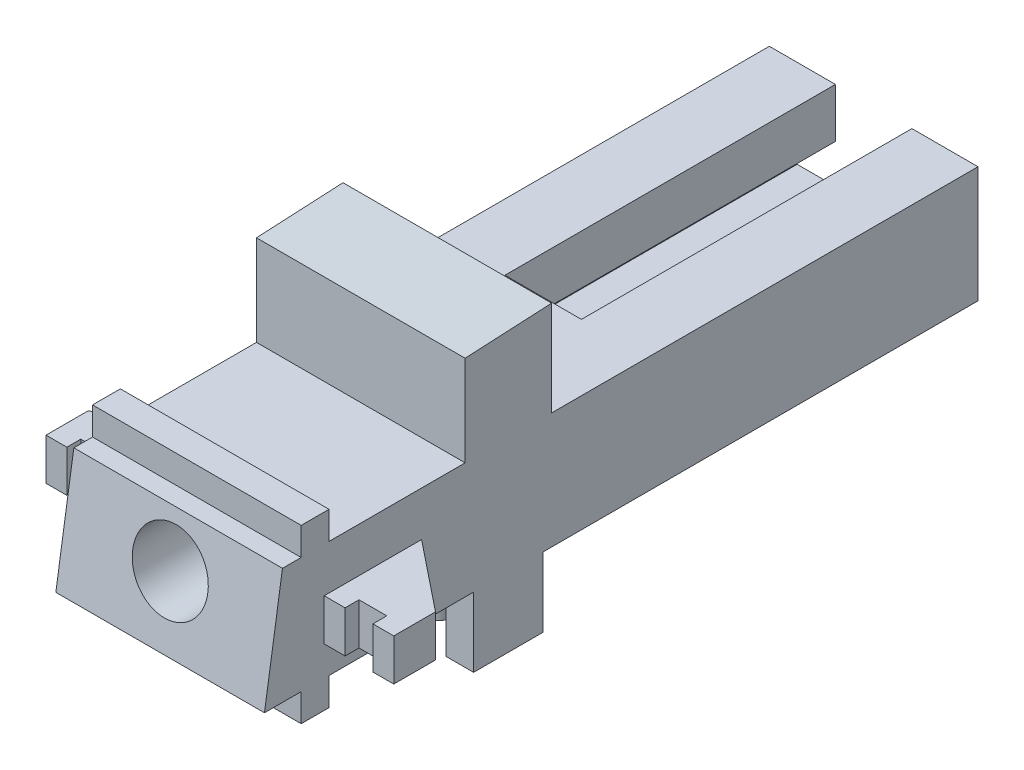
SolidWorks part; units mm, degrees
ref_plane "Front Plane" through (0, 0, 0) normal (0, 0, 1) x (1, 0, 0)
ref_plane "Top Plane" through (0, 0, 0) normal (0, 1, 0) x (1, 0, 0)
ref_plane "Right Plane" through (0, 0, 0) normal (1, 0, 0) x (0, 0, -1)
sketch "Sketch9" plane through (0, 0, 0) normal (0, 0, 1) x (1, 0, 0)
  line L1 (-7.5, 8.35) -> (7.5, 8.35)
  line L2 (-7.5, 8.35) -> (-7.5, 0)
  line L3 (-7.5, 0) -> (7.5, 0)
  line L4 (7.5, 8.35) -> (7.5, 0)
  line L5 (-7.5, 8.35) -> (7.5, 0) construction
  line L6 (-7.5, 0) -> (7.5, 8.35) construction
  point P0 (0, 4.175)
  point P19 (0, 0)
  dimension "D1" = 8.35
  dimension "D2" = 15
extrude "Boss-Extrude4" add sketch "Sketch9" along normal blind 50
sketch "Sketch7" plane through (0, 0, 0) normal (0, 0, 1) x (1, 0, 0)
  line L0 (-5.5, 2) -> (-5.5, 4.8)
  line L1 (-5.5, 4.8) -> (-2.75, 4.8)
  line L2 (-2.75, 4.8) -> (-2.75, 8.35)
  line L3 (-2.75, 8.35) -> (2.75, 8.35) construction
  line L4 (2.75, 8.35) -> (2.75, 4.8)
  line L5 (2.75, 4.8) -> (5.5, 4.8)
  line L6 (5.5, 4.8) -> (5.5, 2)
  line L7 (5.5, 2) -> (-5.5, 2)
  line L9 (7.5, 8.35) -> (-7.5, 8.35) construction
  line L11 (7.5, 0) -> (7.5, 8.35) construction
  line L13 (-2.75, 8.35) -> (2.75, 8.35)
  dimension "D1" = 2.8
  dimension "D2" = 2
  dimension "D3" = 11
  dimension "D4" = 5.5
  dimension "D5" = 2
extrude "Cut-Extrude4" cut sketch "Sketch7" along normal blind 23.76
sketch "Sketch21" plane through (-7.5, 0, 0) normal (-1, 0, 0) x (0, 0, 1)
  line L7 (50, 0) -> (51.2947, 0)
  line L8 (51.2947, 0) -> (50, 8.35)
  line L9 (50, 8.35) -> (50, 0)
extrude "Boss-Extrude9" add sketch "Sketch21" against normal up to surface (15 mm away) up to face at (7.5, 4.175, 25)
sketch "Sketch10" plane through (0, 0, 23.76) normal (0, 0, 1) x (1, 0, 0)
  line L0 (5.5, 2) -> (-5.5, 2) construction
  circle A0 centre (0, 4.7) radius 2.7
  dimension "D1" = 5.4
extrude "Cut-Extrude5" cut sketch "Sketch10" along normal up to surface (26.806 mm away)
sketch "Sketch12" plane through (7.5, 0, 0) normal (1, 0, 0) x (0, 0, -1)
  line L0 (-51.2947, 0) -> (0, 0) construction
  line L1 (-47, 5.14) -> (-44, 5.14)
  line L2 (-47, 5.14) -> (-47, 2.14)
  line L3 (-47, 2.14) -> (-44, 2.14)
  line L4 (-44, 5.14) -> (-44, 2.14)
  line L5 (-47, 5.14) -> (-44, 2.14) construction
  line L6 (-47, 2.14) -> (-44, 5.14) construction
  point P0 (-45.5, 3.64)
  dimension "D1" = 3
  dimension "D2" = 3
  dimension "D3" = 2.14
  dimension "D4" = 3
extrude "Boss-Extrude5" add sketch "Sketch12" along normal blind 5
ref_plane "Plane1" through (0, 0, 0) normal (1, 0, 0) x (0, 0, -1)
sketch "Sketch13" plane through (0, 0, 47) normal (0, 0, 1) x (1, 0, 0)
  line L1 (9, 5.14) -> (11, 5.14)
  line L2 (9, 5.14) -> (9, 2.14)
  line L3 (9, 2.14) -> (11, 2.14)
  line L4 (11, 5.14) -> (11, 2.14)
  line L6 (12.5, 5.14) -> (7.5, 5.14) construction
  line L7 (12.5, 2.14) -> (7.5, 2.14) construction
  point P8 (10, 5.14)
  point P9 (10, 5.14)
  dimension "D2" = 2
extrude "Cut-Extrude6" cut sketch "Sketch13" against normal blind 1
mirror "Mirror2" about plane through (0, 0, 0) normal (1, 0, 0) of "Boss-Extrude5"
mirror "Mirror4" about plane through (0, 0, 0) normal (1, 0, 0) of "Cut-Extrude6"
sketch "Sketch14" plane through (0, 5.14, 0) normal (0, 1, 0) x (1, 0, 0)
  line L0 (12.5, -44) -> (7.5, -40)
  line L1 (7.5, -50) -> (7.5, 0) construction
  line L2 (7.5, -40) -> (7.5, -44)
  line L3 (7.5, -44) -> (12.5, -44)
  dimension "D1" = 4
extrude "Boss-Extrude6" add sketch "Sketch14" against normal up to surface (3 mm away) up to face at (10, 2.14, 46)
mirror "Mirror5" about plane through (0, 0, 0) normal (1, 0, 0) of "Boss-Extrude6"
sketch "Sketch22" plane through (-7.5, 0, 0) normal (-1, 0, 0) x (0, 0, 1)
  line L0 (51.2947, 0) -> (0, 0) construction
  line L1 (48.6551, 0) -> (46.6551, 0)
  line L2 (48.6551, 0) -> (48.6551, -2)
  line L3 (48.6551, -2) -> (46.6551, -2)
  line L4 (46.6551, 0) -> (46.6551, -2)
  line L5 (48.6551, 0) -> (46.6551, -2) construction
  line L6 (48.6551, -2) -> (46.6551, 0) construction
  line L7 (50.6474, 4.175) -> (0, 4.175) construction
  line L8 (51.2947, 0) -> (50, 8.35) construction
  line L9 (0, 8.35) -> (0, 0) construction
  line L10 (48.6551, 10.35) -> (46.6551, 8.35) construction
  line L11 (48.6551, 8.35) -> (46.6551, 10.35) construction
  line L12 (46.6551, 8.35) -> (46.6551, 10.35)
  line L13 (48.6551, 10.35) -> (46.6551, 10.35)
  line L14 (48.6551, 8.35) -> (48.6551, 10.35)
  line L15 (48.6551, 8.35) -> (46.6551, 8.35)
  line L16 (50, 8.35) -> (0, 8.35) construction
  point P0 (47.6551, -1)
  point P18 (47.6551, 9.35)
  dimension "D1" = 2
extrude "Boss-Extrude10" add sketch "Sketch22" against normal up to surface (15 mm away) up to face at (7.5, 4.175, 25.3237)
sketch "Sketch23" plane through (0, 0, 0) normal (0, -1, 0) x (1, 0, 0)
  line L0 (-5.5, 23.76) -> (0, 23.76) construction
  line L2 (-7.5, 23.76) -> (7.5, 23.76) construction
  line L3 (7.5, 46.6551) -> (7.5, 0) construction
  line L4 (-7.5, 46.6551) -> (-7.5, 0) construction
  circle A0 centre (0, 29.26) radius 2.5
  dimension "D2" = 5
  dimension "D1" = 5.5
extrude "Cut-Extrude7" cut sketch "Sketch23" against normal up to surface (2 mm away)
sketch "Sketch24" plane through (0, 0, 0) normal (0, -1, 0) x (1, 0, 0)
  line L0 (5.5, 36.26) -> (7.5, 36.26)
  line L1 (7.5, 46.6551) -> (7.5, 0) construction
  line L2 (7.5, 36.26) -> (7.5, 31.26)
  line L3 (7.5, 31.26) -> (5.5, 31.26)
  line L4 (5.5, 36.26) -> (-5.5, 36.26)
  line L5 (-5.5, 36.26) -> (-5.5, 31.26)
  line L6 (-5.5, 31.26) -> (5.5, 31.26)
  line L7 (5.5, 31.26) -> (5.5, 36.26)
  line L8 (5.5, 36.26) -> (-5.5, 36.26) construction
  line L9 (-5.5, 36.26) -> (-5.5, 31.26)
  line L10 (-5.5, 31.26) -> (5.5, 31.26) construction
  line L11 (5.5, 31.26) -> (5.5, 36.26)
  line L12 (-5.5, 36.26) -> (-7.5, 36.26)
  line L13 (-7.5, 46.6551) -> (-7.5, 0) construction
  line L14 (-7.5, 36.26) -> (-7.5, 31.26)
  line L15 (-7.5, 31.26) -> (-5.5, 31.26)
  line L24 (2.5, 34.76) -> (-2.5, 34.76) construction
  line L25 (2.5, 34.76) -> (-2.5, 34.76) construction
  line L26 (2.5, 32.76) -> (-2.5, 32.76) construction
  line L27 (2.5, 32.76) -> (-2.5, 32.76) construction
  line L28 (2.5, 33.01) -> (-2.5, 33.01)
  line L29 (2.5, 34.51) -> (-2.5, 34.51)
  line L34 (0, 0) -> (0, 51.2947) construction
  line L35 (-7.5, 0) -> (7.5, 0) construction
  line L36 (7.5, 51.2947) -> (-7.5, 51.2947) construction
  arc A0 (2.5, 32.76) -> (2.5, 34.76) centre (2.5, 33.76) ccw construction
  arc A1 (2.5, 32.76) -> (2.5, 34.76) centre (2.5, 33.76) ccw construction
  arc A2 (-2.5, 34.76) -> (-2.5, 32.76) centre (-2.5, 33.76) ccw construction
  arc A3 (-2.5, 34.76) -> (-2.5, 32.76) centre (-2.5, 33.76) ccw construction
  arc A4 (-2.5, 34.51) -> (-2.5, 33.01) centre (-2.5, 33.76) ccw
  arc A5 (2.5, 33.01) -> (2.5, 34.51) centre (2.5, 33.76) ccw
  dimension "D1" = 0
  dimension "D2" = 0.25
extrude "Boss-Extrude11" add sketch "Sketch24" along normal blind 5
sketch "Sketch25" plane through (7.5, 0, 0) normal (1, 0, 0) x (0, 0, -1)
  line L0 (-31.26, -5) -> (-36.26, -5) construction
  line L1 (-30.6504, 8.35) -> (-36.8696, 8.35)
  line L2 (-30.6504, 8.35) -> (-30.6504, 15.1816)
  line L4 (-36.8696, 8.35) -> (-36.8696, 14.8623)
  line L7 (-46.6551, 8.35) -> (0, 8.35) construction
  line L10 (-36.8696, 14.8623) -> (-30.6504, 15.1816)
  point P7 (-33.76, -5)
  point P8 (-33.76, 8.35)
extrude "Boss-Extrude12" add sketch "Sketch25" against normal up to surface (15 mm away) up to face at (-7.5, 2.5063, 38.5984)
